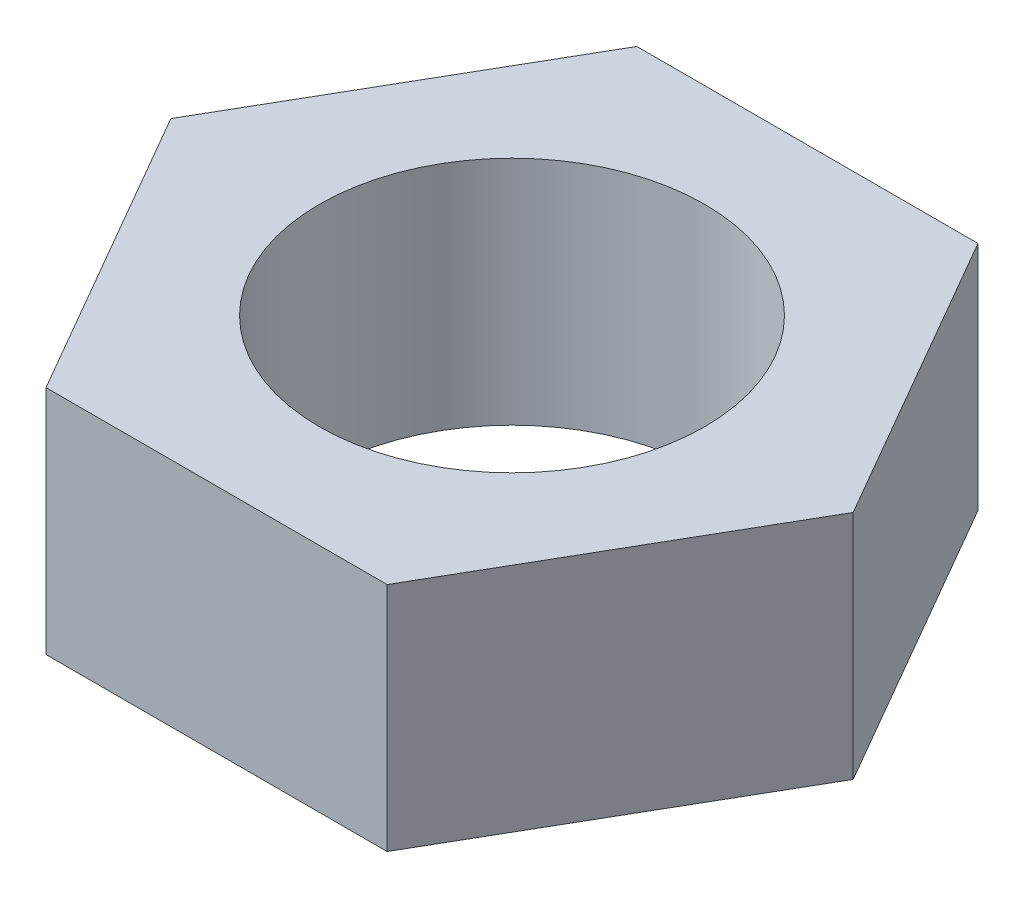
SolidWorks part; units mm, degrees
ref_plane "Front Plane" through (0, 0, 0) normal (0, 0, 1) x (1, 0, 0)
ref_plane "Top Plane" through (0, 0, 0) normal (0, 1, 0) x (1, 0, 0)
ref_plane "Right Plane" through (0, 0, 0) normal (1, 0, 0) x (0, 0, -1)
sketch "Sketch1" plane through (0, 0, 0) normal (0, 1, 0) x (1, 0, 0)
  line L1 (16.8644, 0) -> (8.4322, 14.605)
  line L2 (8.4322, 14.605) -> (-8.4322, 14.605)
  line L3 (-8.4322, 14.605) -> (-16.8644, 0)
  line L4 (-16.8644, 0) -> (-8.4322, -14.605)
  line L5 (-8.4322, -14.605) -> (8.4322, -14.605)
  line L6 (8.4322, -14.605) -> (16.8644, 0)
  circle A0 centre (0, 0) radius 9.525
  circle A1 centre (0, 0) radius 14.605 construction
  dimension "D2" = 19.05
  dimension "D1" = 29.21
extrude "Boss-Extrude1" add sketch "Sketch1" along normal blind 11.43
